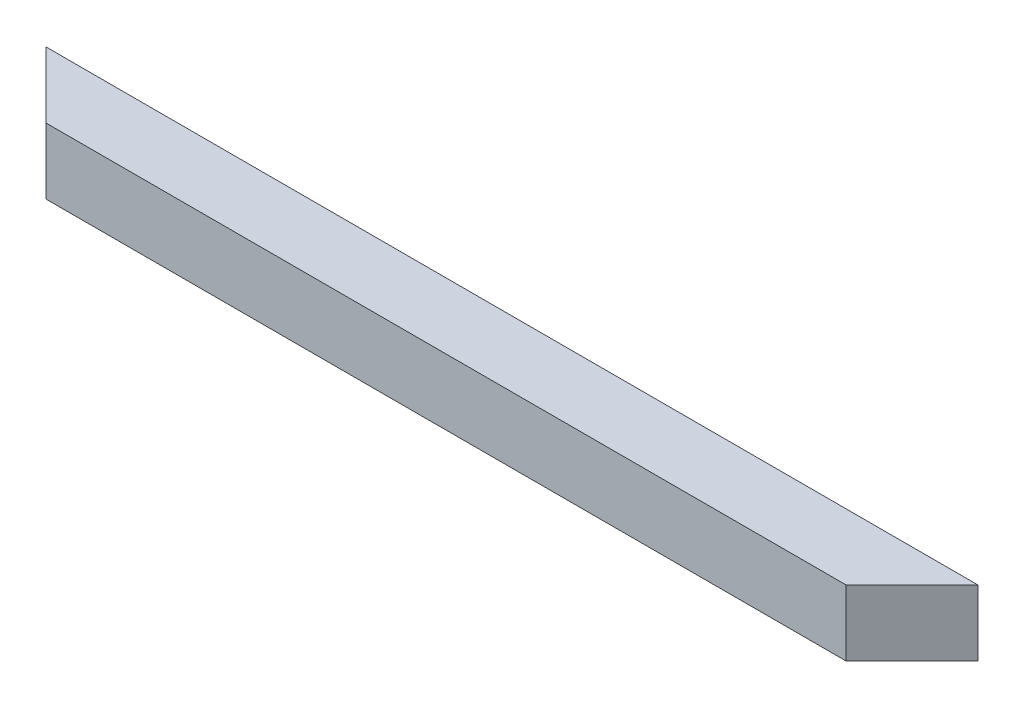
SolidWorks part; units mm, degrees
ref_plane "Front Plane" through (0, 0, 0) normal (0, 0, 1) x (1, 0, 0)
ref_plane "Top Plane" through (0, 0, 0) normal (0, 1, 0) x (1, 0, 0)
ref_plane "Right Plane" through (0, 0, 0) normal (1, 0, 0) x (0, 0, -1)
sketch "Sketch2" plane through (0, 0, 0) normal (0, 1, 0) x (1, 0, 0)
  line L0 (179.6051, 12.7) -> (154.2051, -12.7)
  line L1 (-154.2051, -12.7) -> (154.2051, -12.7)
  line L3 (-179.6051, 12.7) -> (179.6051, 12.7)
  line L5 (-155.8825, -11.0226) -> (179.6051, 12.7) construction
  line L6 (-179.6051, 12.7) -> (155.8825, -11.0226) construction
  line L7 (-179.6051, 12.7) -> (-154.2051, -12.7)
  point P0 (0, 0)
  dimension "D1" = 359.2101
extrude "Boss-Extrude1" add sketch "Sketch2" along normal blind 25.4
